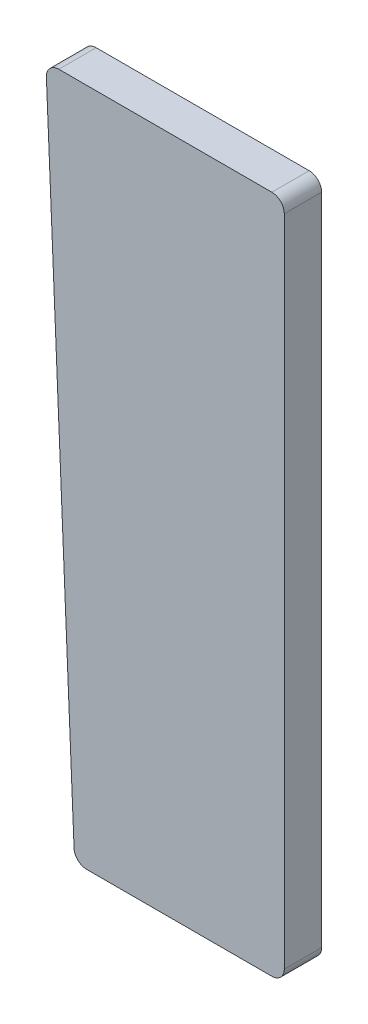
SolidWorks part; units mm, degrees
ref_plane "Front Plane" through (0, 0, 0) normal (0, 0, 1) x (1, 0, 0)
ref_plane "Top Plane" through (0, 0, 0) normal (0, 1, 0) x (1, 0, 0)
ref_plane "Right Plane" through (0, 0, 0) normal (1, 0, 0) x (0, 0, -1)
sketch "Sketch1" plane through (0, 0, 0) normal (0, 0, 1) x (1, 0, 0)
  line L0 (0, 0) -> (0, 299.0497)
  line L1 (0, 299.0497) -> (-191.735, 299.0497)
  line L2 (0, 0) -> (0, -246.9503)
  line L3 (0, -246.9503) -> (-168.625, -246.9503)
  line L4 (-191.735, 299.0497) -> (-168.625, -246.9503)
  point P3 (0, 0)
  dimension "D1" = 191.735
  dimension "D2" = 168.625
  dimension "D3" = 546
extrude "Boss-Extrude1" add sketch "Sketch1" along normal blind 30
fillet "Fillet1" radius 10 2 edges at (0, 299.0497, 15) (-191.735, 299.0497, 15)
fillet "Fillet2" radius 10 2 edges at (-168.625, -246.9503, 15) (0, -246.9503, 15)
